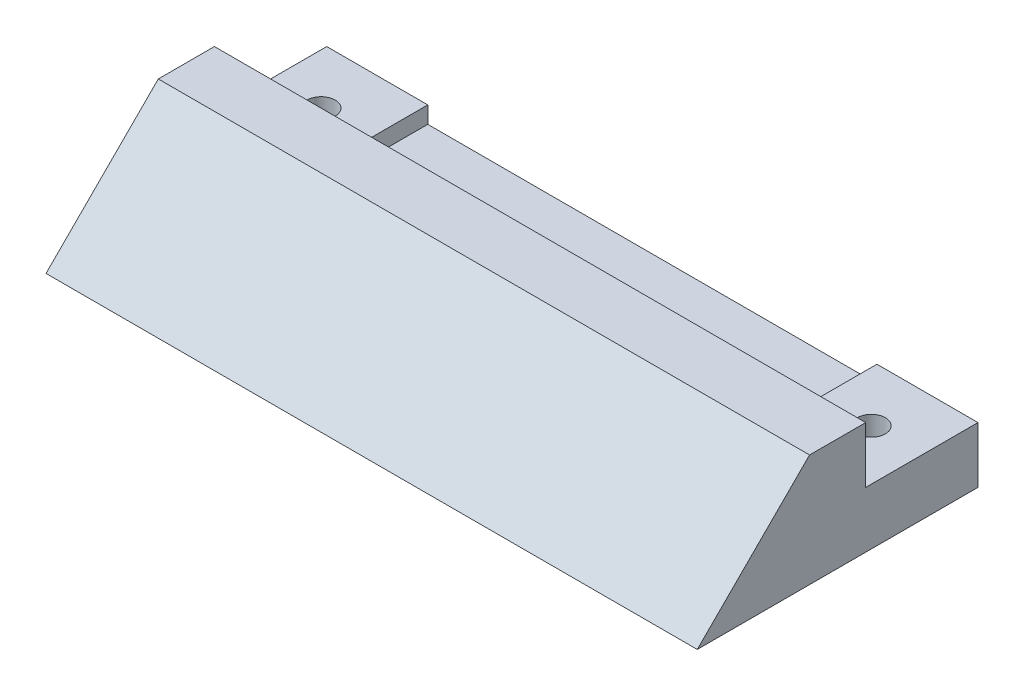
SolidWorks part; units mm, degrees
material "1060 Alloy"
ref_plane "Front Plane" through (0, 0, 0) normal (0, 0, 1) x (1, 0, 0)
ref_plane "Top Plane" through (0, 0, 0) normal (0, 1, 0) x (1, 0, 0)
ref_plane "Right Plane" through (0, 0, 0) normal (1, 0, 0) x (0, 0, -1)
sketch "Sketch1" plane through (0, 0, 0) normal (1, 0, 0) x (0, 0, -1)
  line L0 (0, 0) -> (10, 10)
  line L1 (10, 10) -> (25, 10)
  line L2 (25, 10) -> (25, 0)
  line L3 (25, 0) -> (0, 0)
  dimension "D1" = 45
  dimension "D2" = 10
  dimension "D3" = 15
extrude "Boss-Extrude1" add sketch "Sketch1" along normal blind 58
sketch "Sketch3" plane through (0, 10, 0) normal (0, 1, 0) x (1, 0, 0)
  line L0 (58, 25) -> (0, 25) construction
  line L1 (9, 25) -> (49, 25)
  line L2 (9, 25) -> (9, 15)
  line L3 (9, 15) -> (49, 15)
  line L4 (49, 25) -> (49, 15)
  line L7 (29, 0) -> (29, 15) construction
  line L8 (58, 0) -> (0, 0) construction
  dimension "D2" = 40
  dimension "D3" = 10
extrude "Cut-Extrude2" cut sketch "Sketch3" against normal blind 6.5
sketch "Sketch4" plane through (0, 3.5, 0) normal (0, 1, 0) x (1, 0, 0)
  line L0 (9, 15) -> (49, 15) construction
  line L1 (9, 25) -> (9, 15) construction
  line L3 (49, 15) -> (49, 25) construction
  line L4 (29, 25) -> (29, 20) construction
  line L5 (49, 25) -> (9, 25) construction
  circle A0 centre (14, 20) radius 1.25
  circle A1 centre (29, 20) radius 1.25
  circle A2 centre (44, 20) radius 1.25
  dimension "D1" = 2.5
  dimension "D2" = 5
  dimension "D3" = 5
  dimension "D5" = 5
extrude "Cut-Extrude3" cut sketch "Sketch4" against normal up to next
sketch "Sketch5" plane through (0, 10, 0) normal (0, 1, 0) x (1, 0, 0)
  line L0 (58, 25) -> (58, 10) construction
  line L1 (0, 25) -> (58, 25)
  line L2 (0, 25) -> (0, 15)
  line L3 (0, 15) -> (58, 15)
  line L4 (58, 25) -> (58, 15)
  line L5 (9, 15) -> (49, 15) construction
extrude "Cut-Extrude4" cut sketch "Sketch5" against normal offset from surface (5 mm away) 1.5 up to face at (44, 3.5, -18.75)
sketch "Sketch6" plane through (0, 5, 0) normal (0, 1, 0) x (1, 0, 0)
  line L0 (0, 25) -> (9, 25) construction
  line L1 (0, 15) -> (0, 25) construction
  line L4 (58, 25) -> (58, 15) construction
  circle A0 centre (4.5, 20) radius 1.25
  circle A1 centre (53.5, 20) radius 1.25
  dimension "D1" = 2.5
  dimension "D2" = 5
  dimension "D3" = 4.5
  dimension "D4" = 4.5
extrude "Cut-Extrude5" cut sketch "Sketch6" against normal up to next
fillet "Fillet1" radius 3 2 edges at (49, 4.25, -15) (9, 4.25, -15)
